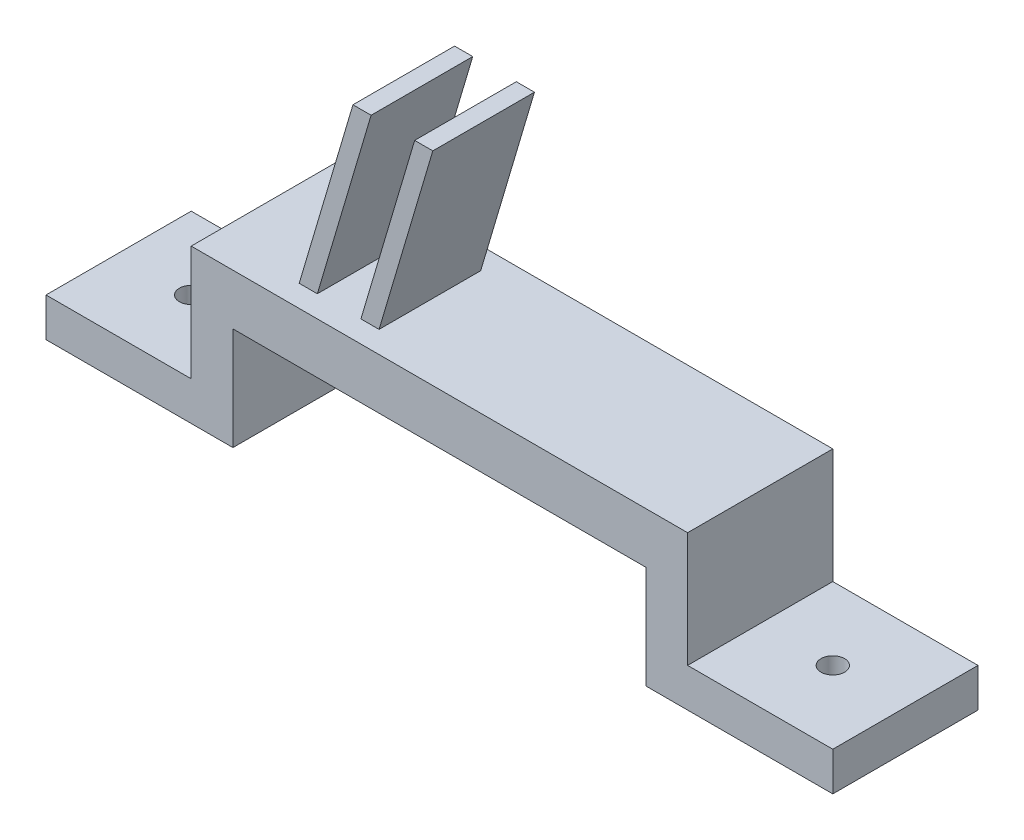
SolidWorks part; units mm, degrees
ref_plane "前视基准面" through (0, 0, 0) normal (0, 0, 1) x (1, 0, 0)
ref_plane "上视基准面" through (0, 0, 0) normal (0, 1, 0) x (1, 0, 0)
ref_plane "右视基准面" through (0, 0, 0) normal (1, 0, 0) x (0, 0, -1)
sketch "草图2" plane through (0, 0, 0) normal (0, 0, 1) x (1, 0, 0)
  line L1 (-20.1082, 12.6633) -> (34.5918, 12.6633)
  line L2 (-20.1082, 12.6633) -> (-20.1082, -4.2667)
  line L3 (-20.1082, -4.2667) -> (34.5918, -4.2667)
  line L4 (34.5918, 12.6633) -> (34.5918, -4.2667)
  line L5 (-15.5082, 8.0633) -> (29.9918, 8.0633)
  line L6 (-15.5082, 8.0633) -> (-15.5082, -4.2667)
  line L7 (-15.5082, -4.2667) -> (29.9918, -4.2667)
  line L8 (29.9918, 8.0633) -> (29.9918, -4.2667)
  dimension "D1" = 54.7
  dimension "D2" = 16.93
  dimension "D3" = 4.6
  dimension "D4" = 45.5
  dimension "D5" = 4.6
  dimension "D6" = 4.6
extrude "凸台-拉伸1" add sketch "草图2" along normal blind 16 contours L5 L8 L3 L4 L1 L2 L6
sketch "草图3" plane through (-20.1082, 0, 0) normal (-1, 0, 0) x (0, 0, 1)
  line L0 (16, -4.2667) -> (0, -4.2667) construction
  line L3 (0, -4.2667) -> (8, -4.2667)
  line L9 (0, 0) -> (16, 0)
  line L10 (0, 0) -> (0, -4.2667)
  line L11 (0, -4.2667) -> (16, -4.2667)
  line L12 (16, 0) -> (16, -4.2667)
  dimension "D1" = 4.2667
sketch "草图5" plane through (-20.1082, 0, 0) normal (-1, 0, 0) x (0, 0, 1)
extrude "凸台-拉伸3" add sketch "草图3" along normal blind 16 contours L10 L9 L12 L11
sketch "草图17" plane through (0, 0, 0) normal (0, 1, 0) x (1, 0, 0)
  point P0 (-27.8685, -8.0352)
  point P2 (-27.8685, -8.0352)
sketch "草图22" plane through (0, 0, 0) normal (0, 1, 0) x (1, 0, 0)
sketch "草图23" plane through (34.5918, 0, 0) normal (1, 0, 0) x (0, 0, -1)
  line L1 (0, 0) -> (-16, 0)
  line L2 (0, 0) -> (0, -4.2667)
  line L3 (0, -4.2667) -> (-16, -4.2667)
  line L4 (-16, 0) -> (-16, -4.2667)
  dimension "D1" = 4.2667
extrude "凸台-拉伸4" add sketch "草图23" along normal blind 16
sketch "草图24" plane through (0, 0, 0) normal (0, 1, 0) x (1, 0, 0)
  line L0 (34.5918, 0) -> (50.5918, -16) construction
  line L1 (50.5918, -16) -> (50.5918, 0) construction
  line L2 (50.5918, 0) -> (34.5918, -16) construction
  point P13 (42.5918, -8)
hole_wizard "Ø2.0mm 暗销孔2" positions "草图24" profile "草图25" hole size "Ø2.0" standard "GB" end condition through all
sketch "草图25" plane through (42.5918, 0, 8) normal (1, 0, 0) x (0, 0, 1)
  line L0 (0, 0) -> (0, 4.2667)
  line L1 (0, 4.2667) -> (1.3, 4.2667)
  line L2 (1.3, 4.2667) -> (1.3, 0)
  line L5 (1.3, 0) -> (0, 0)
  line L11 (0, -6.35) -> (0, 107.95) construction
  dimension "通孔孔直径" = 2.6
  dimension "通孔孔深度" = 4.2667
sketch "草图28" plane through (0, 0, 16) normal (0, 0, 1) x (1, 0, 0)
sketch "草图29" plane through (0, 0, 16) normal (0, 0, 1) x (1, 0, 0)
sketch "草图30" plane through (0, 0, 0) normal (0, 1, 0) x (1, 0, 0)
  line L0 (-36.1082, 0) -> (-20.1082, -16) construction
  line L2 (-20.1082, 0) -> (-36.1082, -16) construction
sketch "草图31" plane through (0, 0, 0) normal (0, 1, 0) x (1, 0, 0)
  line L0 (-36.1082, 0) -> (-20.1082, -16) construction
  point P0 (-28.1082, -8)
hole_wizard "Ø2.0mm 暗销孔3" positions "草图31" profile "草图32" hole size "Ø2.0" standard "BSI" end condition through all
sketch "草图32" plane through (-28.1082, 0, 8) normal (1, 0, 0) x (0, 0, 1)
  line L0 (0, 0) -> (0, 4.2667)
  line L1 (0, 4.2667) -> (1.3, 4.2667)
  line L2 (1.3, 4.2667) -> (1.3, 0)
  line L5 (1.3, 0) -> (0, 0)
  line L11 (0, -6.35) -> (0, 107.95) construction
  dimension "通孔孔直径" = 2.6
  dimension "通孔孔深度" = 4.2667
sketch "草图33" plane through (0, 8.0633, 0) normal (0, -1, 0) x (1, 0, 0)
  line L1 (-15.5082, 16) -> (29.9918, 16)
  line L2 (-15.5082, 16) -> (-15.5082, 0)
  line L3 (-15.5082, 0) -> (29.9918, 0)
  line L4 (29.9918, 16) -> (29.9918, 0)
extrude "凸台-拉伸5" add sketch "草图33" along normal blind 1
sketch "草图34" plane through (0, 12.6633, 0) normal (0, 1, 0) x (1, 0, 0)
  line L0 (-20.1082, 0) -> (34.5918, 0) construction
  line L2 (-20.1082, -13.6) -> (-20.1082, -2.4)
  line L3 (-20.1082, -2.4) -> (8.4306, -2.4)
  line L4 (8.4306, -13.6) -> (8.4306, -2.4)
  line L6 (-20.1082, -13.6) -> (8.4306, -13.6)
  dimension "D1" = 2.4
extrude "凸台-拉伸6" add sketch "草图34" along normal blind 20
sketch "草图35" plane through (0, 0, 16) normal (0, 0, 1) x (1, 0, 0)
  line L0 (8.4306, 12.6633) -> (-1.8082, 12.6633)
  line L1 (-20.1082, 12.6633) -> (-20.1082, 0) construction
  line L2 (-3.8082, 16.327) -> (-3.8082, 9.7039) construction
  line L3 (-1.8082, 16.327) -> (-1.8082, 9.7039) construction
  line L4 (-8.6082, 16.327) -> (-8.6082, 9.5545) construction
  line L5 (-10.6082, 16.5511) -> (-10.6082, 9.1312) construction
  line L6 (-3.8082, 16.327) -> (-3.8082, 10.345)
  line L7 (-3.8082, 12.6633) -> (2.1161, 32.6633)
  line L8 (-20.1082, 32.6633) -> (8.4306, 32.6633) construction
  line L9 (-20.1082, 12.6633) -> (34.5918, 12.6633) construction
  line L10 (-1.8082, 12.6633) -> (4.1161, 32.6633)
  line L11 (-8.6082, 12.6633) -> (-2.6839, 32.6633)
  line L12 (-10.6082, 12.6633) -> (-4.6839, 32.6633)
  line L13 (-10.6082, 12.6633) -> (-20.1082, 12.6633)
  line L14 (2.1161, 32.6633) -> (4.1161, 32.6633)
  line L15 (-3.8082, 12.6633) -> (-8.6082, 12.6633)
  line L16 (-2.6839, 32.6633) -> (2.1161, 32.6633)
  line L17 (4.1161, 32.6633) -> (8.4306, 32.6633)
  line L18 (8.4306, 32.6633) -> (8.4306, 12.6633)
  line L19 (-4.6839, 32.6633) -> (-20.1082, 32.6633)
  line L20 (-20.1082, 32.6633) -> (-20.1082, 12.6633)
  dimension "D1" = 16.3
  dimension "D2" = 2
  dimension "D3" = 4.8
  dimension "D4" = 2
  dimension "D5" = 73.5
  dimension "D6" = 73.5
  dimension "D7" = 73.5
  dimension "D8" = 73.5
extrude "切除-拉伸1" cut sketch "草图35" against normal blind 20
